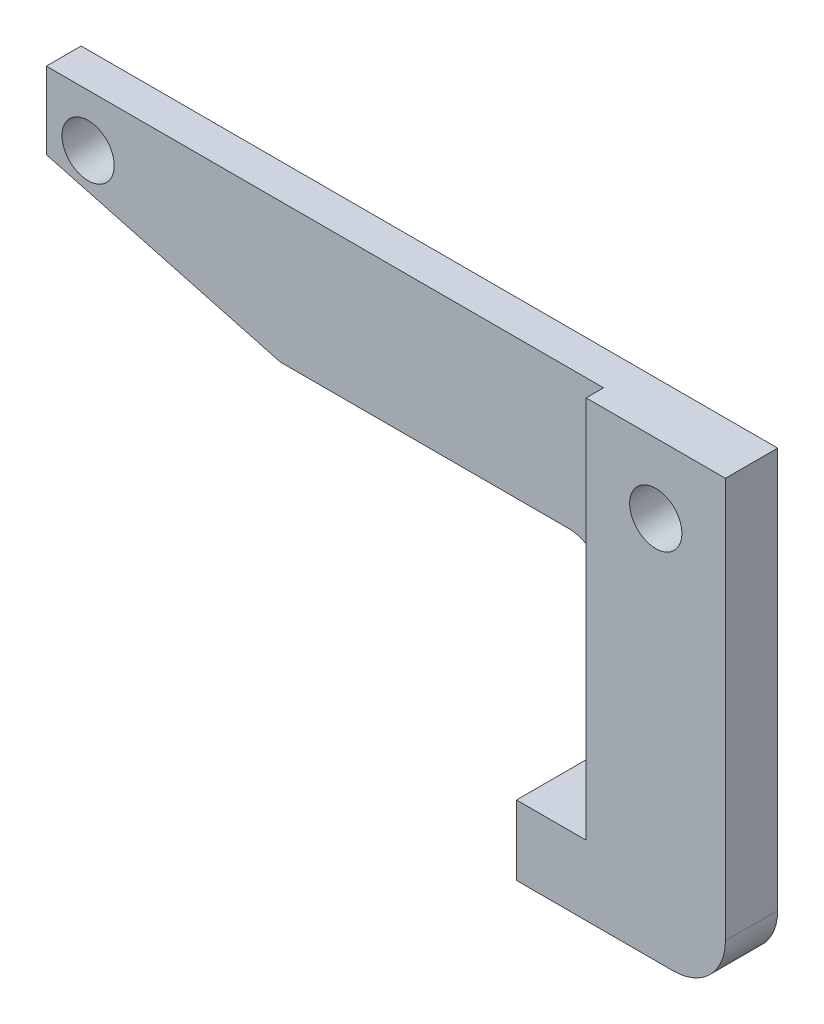
SolidWorks part; units mm, degrees
ref_plane "Front" through (0, 0, 0) normal (0, 0, 1) x (1, 0, 0)
ref_plane "Top" through (0, 0, 0) normal (0, 1, 0) x (1, 0, 0)
ref_plane "Right" through (0, 0, 0) normal (1, 0, 0) x (0, 0, -1)
other "Configuration Table"
sketch "Sketch1" plane through (0, 0, 0) normal (0, 0, 1) x (1, 0, 0)
  line L1 (-114.3, 12.7) -> (12.7, 12.7)
  line L2 (-114.3, 12.7) -> (-114.3, -12.7)
  line L3 (-114.3, -12.7) -> (-12.7, -12.7)
  line L4 (12.7, 12.7) -> (12.7, -69.85)
  line L6 (-12.7, -12.7) -> (-12.7, -57.15)
  line L9 (-12.7, -57.15) -> (-25.4, -57.15)
  line L11 (12.7, -69.85) -> (-25.4, -69.85)
  line L12 (-25.4, -57.15) -> (-25.4, -69.85)
  dimension "D1" = 25.4
  dimension "D2" = 127
  dimension "D3" = 44.45
  dimension "D4" = 82.55
  dimension "D5" = 12.7
  dimension "D6" = 12.7
  dimension "D7" = 38.1
  dimension "D8" = 25.4
extrude "Base-Extrude" add sketch "Sketch1" along normal blind 12.7
sketch "Sketch2" plane through (0, 0, 12.7) normal (0, 0, 1) x (1, 0, 0)
  circle A0 centre (0, 0) radius 4.7625
  dimension "D1" = 9.525
extrude "Cut-Extrude1" cut sketch "Sketch2" against normal through all
sketch "Sketch3" plane through (0, 0, 12.7) normal (0, 0, 1) x (1, 0, 0)
  line L1 (12.7, 12.7) -> (-114.3, 12.7) construction
  line L2 (-114.3, 12.7) -> (-114.3, -12.7) construction
  circle A0 centre (-106.68, 3.175) radius 4.7625
  dimension "D1" = 9.525
  dimension "D2" = 9.525
  dimension "D3" = 7.62
extrude "Cut-Extrude2" cut sketch "Sketch3" against normal through all
chamfer "Chamfer1" distance 11.43 angle 75 1 edges at (-114.3, -12.7, 6.35)
sketch "Sketch4" plane through (0, 0, 12.7) normal (0, 0, 1) x (1, 0, 0)
  line L1 (-12.7, -12.7) -> (-114.3, -12.7)
  line L2 (-12.7, -12.7) -> (-12.7, 12.7)
  line L3 (-12.7, 12.7) -> (-114.3, 12.7)
  line L4 (-114.3, -12.7) -> (-114.3, 12.7)
extrude "Cut-Extrude3" cut sketch "Sketch4" against normal blind 3.175
fillet "Fillet1" radius 9.525 1 edges at (12.7, -69.85, 6.35)
fillet "Fillet2" radius 6.35 1 edges at (-12.7, -12.7, 4.7625)
chamfer "Chamfer2" distance 3.175 angle 45 4 edges at (12.7, -23.8125, 0) (9.9102, -67.0602, 0) (-50.8, 12.7, 0) (-11.1125, -69.85, 0)
sketch "Sketch5" plane through (0, 0, 0) normal (0, 0, -1) x (-1, 0, 0)
  circle A0 centre (0, 0) radius 9.525
  dimension "D1" = 19.05
extrude "Cut-Extrude4" cut sketch "Sketch5" against normal blind 4.445
